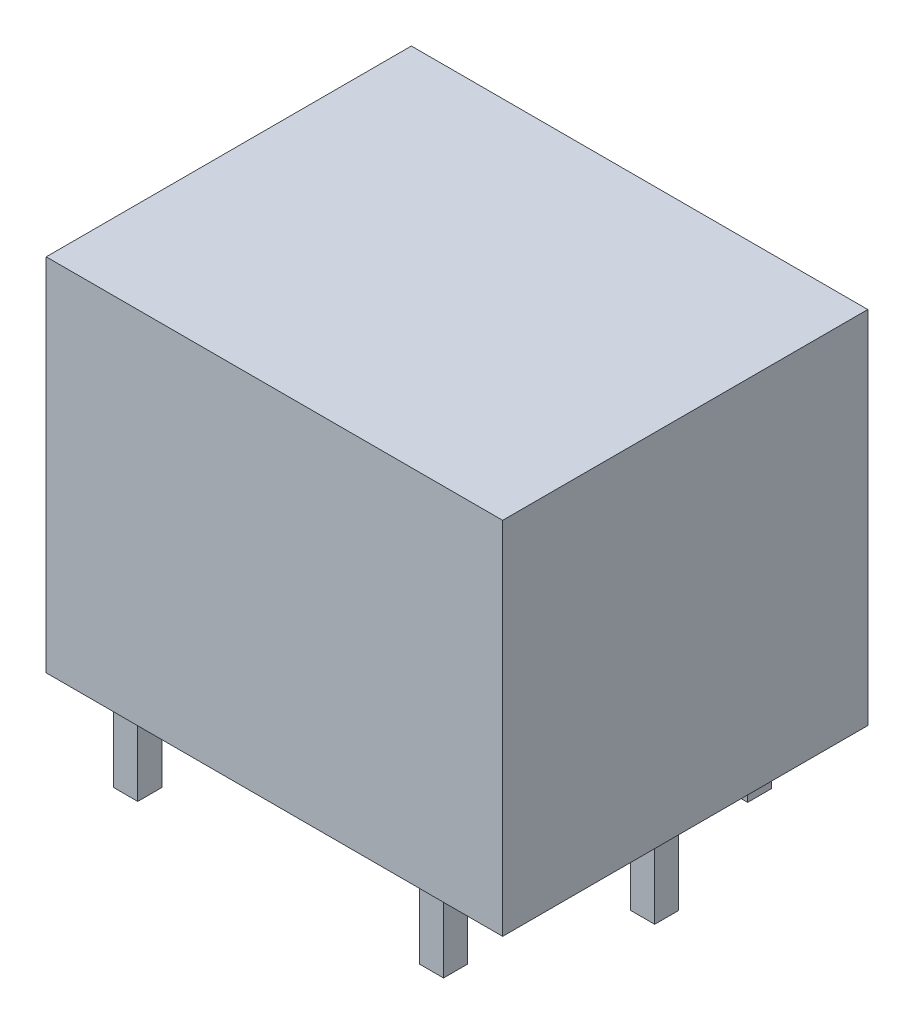
SolidWorks part; units mm, degrees
ref_plane "前视基准面" through (0, 0, 0) normal (0, 0, 1) x (1, 0, 0)
ref_plane "上视基准面" through (0, 0, 0) normal (0, 1, 0) x (1, 0, 0)
ref_plane "右视基准面" through (0, 0, 0) normal (1, 0, 0) x (0, 0, -1)
sketch "草图1" plane through (0, 0, 0) normal (0, 1, 0) x (1, 0, 0)
  line L0 (0, 41.7773) -> (0, -45.7415) construction
  line L1 (-9.5, 7.6) -> (9.5, 7.6)
  line L2 (-9.5, 7.6) -> (-9.5, -7.6)
  line L3 (-9.5, -7.6) -> (9.5, -7.6)
  line L4 (9.5, 7.6) -> (9.5, -7.6)
  line L5 (-48.486, 0) -> (58.5492, 0) construction
  dimension "D1" = 19
  dimension "D2" = 15.2
extrude "拉伸1" add sketch "草图1" along normal blind 15
sketch "草图2" plane through (0, 0, 0) normal (0, -1, 0) x (1, 0, 0)
  line L0 (9.9294, 0) -> (-10.2276, 0) construction
  line L1 (8.73, -0.5) -> (7.73, -0.5)
  line L2 (8.73, -0.5) -> (8.73, 0.5)
  line L3 (8.73, 0.5) -> (7.73, 0.5)
  line L4 (7.73, -0.5) -> (7.73, 0.5)
  line L5 (8.23, -1.6251) -> (8.23, 1.1288) construction
  line L6 (9.5, 7.6) -> (9.5, -7.6) construction
  line L7 (8.0786, 6.33) -> (-8.6507, 6.33) construction
  line L8 (6.27, 6.83) -> (5.27, 6.83)
  line L9 (6.27, 6.83) -> (6.27, 5.83)
  line L10 (6.27, 5.83) -> (5.27, 5.83)
  line L11 (5.27, 6.83) -> (5.27, 5.83)
  line L12 (-9.5, 7.6) -> (9.5, 7.6) construction
  line L13 (5.77, 4.8939) -> (5.77, 7.944) construction
  line L14 (-6.46, 6.83) -> (-7.46, 6.83)
  line L15 (-6.46, 6.83) -> (-6.46, 5.83)
  line L16 (-6.46, 5.83) -> (-7.46, 5.83)
  line L17 (-7.46, 6.83) -> (-7.46, 5.83)
  line L18 (-6.96, 7.128) -> (-6.96, 5.1977) construction
  line L19 (-9.5, -7.6) -> (-9.5, 7.6) construction
  line L20 (-7.46, -6.83) -> (-7.46, -5.83)
  line L21 (-6.46, -5.83) -> (-7.46, -5.83)
  line L22 (-6.46, -6.83) -> (-6.46, -5.83)
  line L23 (-6.46, -6.83) -> (-7.46, -6.83)
  line L24 (5.27, -6.83) -> (5.27, -5.83)
  line L25 (6.27, -5.83) -> (5.27, -5.83)
  line L26 (6.27, -6.83) -> (6.27, -5.83)
  line L27 (6.27, -6.83) -> (5.27, -6.83)
  dimension "D1" = 1
  dimension "D2" = 1
  dimension "D3" = 1.27
  dimension "D4" = 1
  dimension "D5" = 1
  dimension "D6" = 1.27
  dimension "D7" = 3.73
  dimension "D8" = 1
  dimension "D9" = 1
  dimension "D10" = 2.54
extrude "拉伸2" add sketch "草图2" along normal blind 3.5
